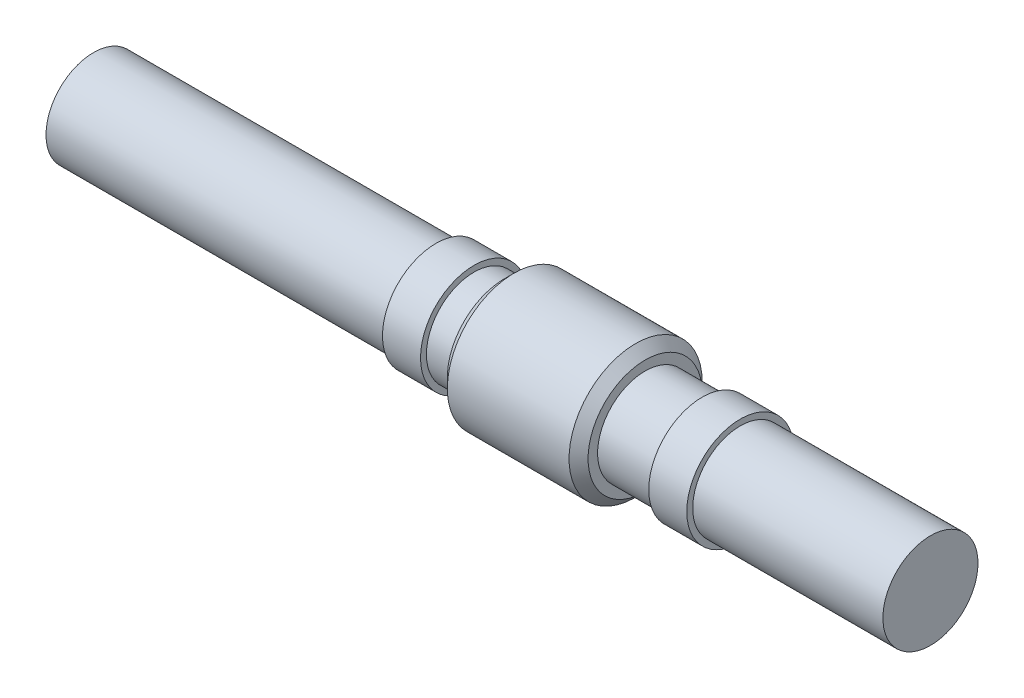
SolidWorks part; units mm, degrees
ref_plane "Frontal" through (0, 0, 0) normal (0, 0, 1) x (1, 0, 0)
ref_plane "Superior" through (0, 0, 0) normal (0, 1, 0) x (1, 0, 0)
ref_plane "Izquierda" through (0, 0, 0) normal (1, 0, 0) x (0, 0, -1)
sketch "Croquis1" plane through (0, 0, 0) normal (1, 0, 0) x (0, 0, -1)
  circle A0 centre (0, 0) radius 35
  dimension "D1" = 70
extrude "Saliente-Extruir1" add sketch "Croquis1" along normal mid plane 74
ref_plane "Plano1" through (7, 0, 0) normal (-1, 0, 0) x (0, 0, 1)
chamfer "Chaflán1" distance 5 angle 45 2 edges at (37, 0, -35) (-37, 0, -35)
sketch "Croquis2" plane through (-37, 0, 0) normal (-1, 0, 0) x (0, 0, 1)
  circle A0 centre (0, 0) radius 25
  dimension "D1" = 50
extrude "Saliente-Extruir2" add sketch "Croquis2" along normal blind 16
sketch "Croquis3" plane through (-53, 0, 0) normal (-1, 0, 0) x (0, 0, 1)
  circle A0 centre (0, 0) radius 28.1
  dimension "D1" = 56.2
extrude "Saliente-Extruir3" add sketch "Croquis3" along normal blind 120
chamfer "Chaflán2" [suppressed] distance 2.5 angle 45
sketch "Croquis4" plane through (37, 0, 0) normal (1, 0, 0) x (0, 0, -1)
  circle A0 centre (0, 0) radius 25
  dimension "D1" = 50
extrude "Saliente-Extruir4" add sketch "Croquis4" along normal blind 30
sketch "Croquis5" plane through (67, 0, 0) normal (1, 0, 0) x (0, 0, -1)
  circle A0 centre (0, 0) radius 28.1
  dimension "D1" = 56.2
extrude "Saliente-Extruir5" add sketch "Croquis5" along normal blind 120
chamfer "Chaflán3" [suppressed] distance 2.5 angle 45
sketch "Croquis6" plane through (-173, 0, 0) normal (-1, 0, 0) x (0, 0, 1)
  circle A0 centre (0, 0) radius 25
  circle A1 centre (0, 0) radius 28.1
extrude "Cortar-Extruir1" cut sketch "Croquis6" against normal blind 100
sketch "Croquis8" plane through (187, 0, 0) normal (1, 0, 0) x (0, 0, -1)
  circle A0 centre (0, 0) radius 25
  circle A1 centre (0, 0) radius 28.1
extrude "Cortar-Extruir2" cut sketch "Croquis8" against normal blind 100
sketch "Croquis9" plane through (-173, 0, 0) normal (-1, 0, 0) x (0, 0, 1)
  circle A0 centre (0, 0) radius 25
  dimension "D1" = 50
extrude "Saliente-Extruir6" add sketch "Croquis9" along normal blind 80
